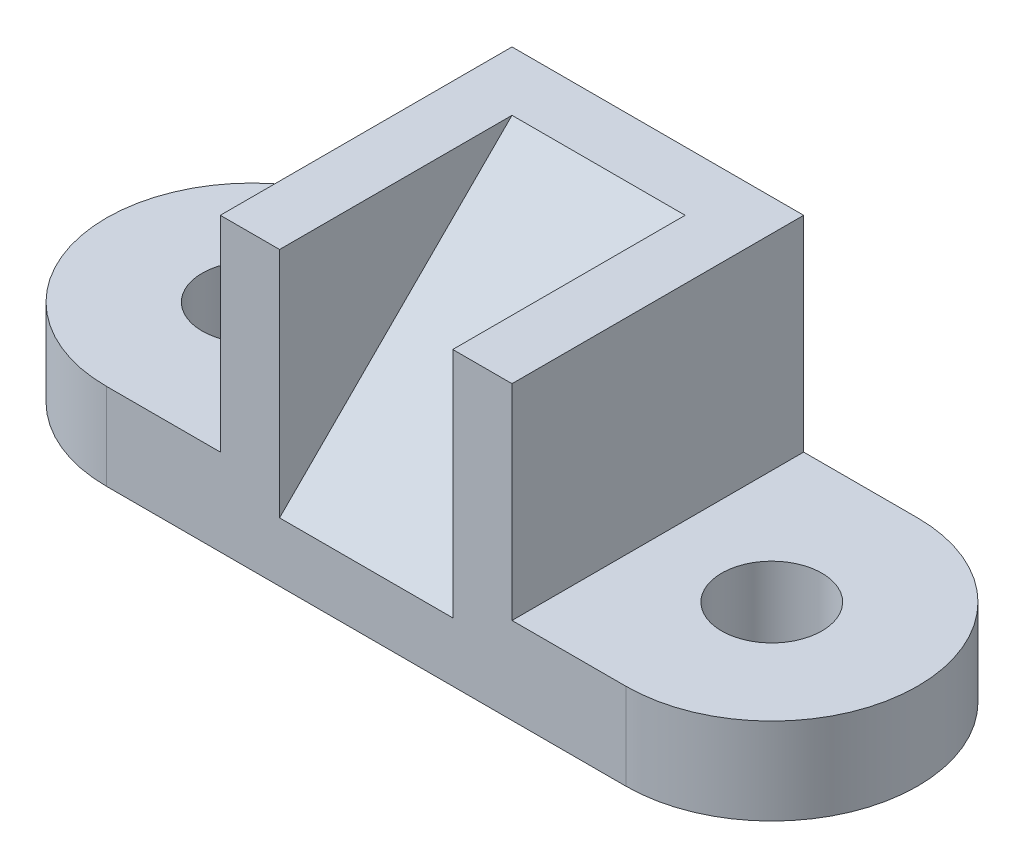
SolidWorks part; units mm, degrees
ref_plane "Front Plane" through (0, 0, 0) normal (0, 0, 1) x (1, 0, 0)
ref_plane "Top Plane" through (0, 0, 0) normal (0, 1, 0) x (1, 0, 0)
ref_plane "Right Plane" through (0, 0, 0) normal (1, 0, 0) x (0, 0, -1)
sketch "Sketch1" plane through (0, 0, 0) normal (0, 1, 0) x (1, 0, 0)
  line L0 (-57, 0) -> (57, 0) construction
  line L1 (-57, 32) -> (57, 32)
  line L2 (-57, -32) -> (57, -32)
  arc A0 (-57, 32) -> (-57, -32) centre (-57, 0) ccw
  arc A1 (57, -32) -> (57, 32) centre (57, 0) ccw
  circle A2 centre (-57, 0) radius 11
  circle A3 centre (57, 0) radius 11
  point P3 (0, 0)
  point P12 (0, 0)
  dimension "D1" = 22
  dimension "D2" = 22
  dimension "D3" = 32
  dimension "D4" = 114
extrude "Boss-Extrude1" add sketch "Sketch1" along normal blind 19
sketch "Sketch2" plane through (0, 19, 0) normal (0, 1, 0) x (1, 0, 0)
  line L0 (57, 32) -> (-57, 32) construction
  line L1 (32, -32) -> (-32, -32)
  line L2 (32, -32) -> (32, 32)
  line L3 (32, 32) -> (-32, 32)
  line L4 (-32, -32) -> (-32, 32)
  line L5 (32, -32) -> (-32, 32) construction
  line L6 (32, 32) -> (-32, -32) construction
  point P0 (0, 0)
  dimension "D1" = 64
  dimension "D2" = 64
extrude "Boss-Extrude2" add sketch "Sketch2" along normal blind 45
sketch "Sketch4" plane through (-32, 0, 0) normal (-1, 0, 0) x (0, 0, 1)
  line L0 (-19, 64) -> (32, 13)
  line L1 (-32, 64) -> (32, 64) construction
  line L2 (32, 19) -> (32, 0) construction
  line L3 (32, 13) -> (32, 64)
  line L4 (32, 64) -> (-19, 64)
  dimension "D1" = 13
  dimension "D2" = 13
extrude "Cut-Extrude1" cut sketch "Sketch4" against normal blind 38 from offset 13
